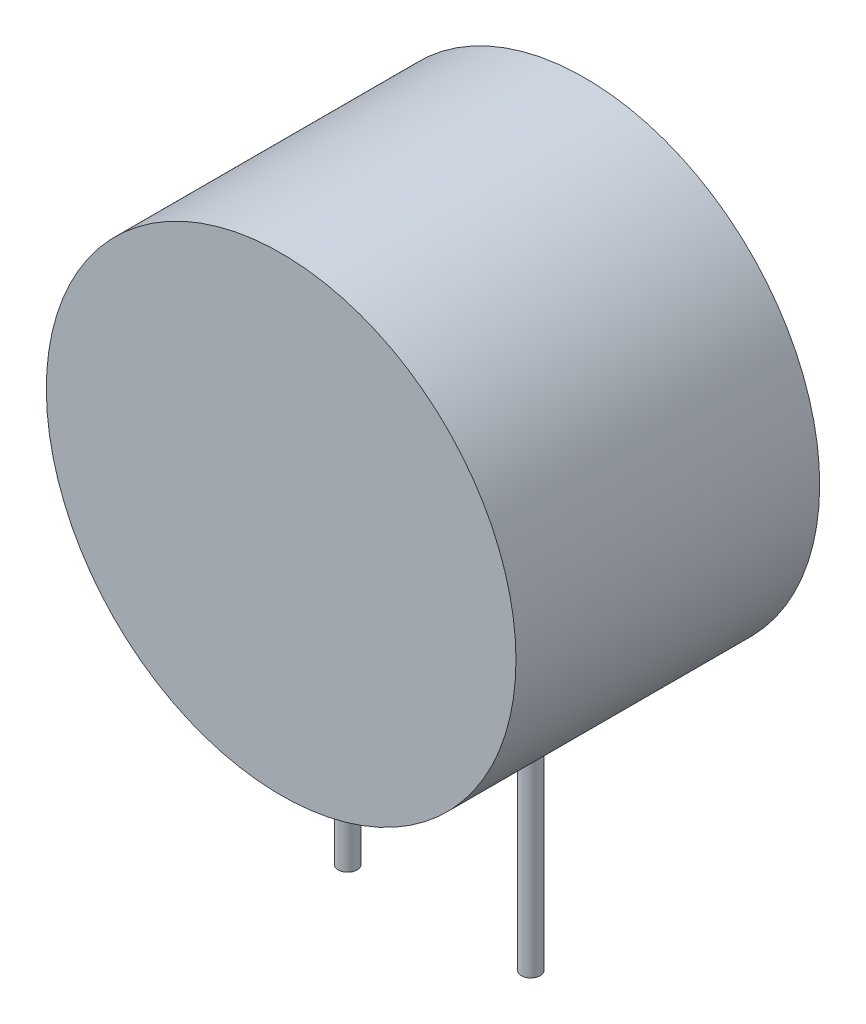
SolidWorks part; units mm, degrees
ref_plane "Front Plane" through (0, 0, 0) normal (0, 0, 1) x (1, 0, 0)
ref_plane "Top Plane" through (0, 0, 0) normal (0, 1, 0) x (1, 0, 0)
ref_plane "Right Plane" through (0, 0, 0) normal (1, 0, 0) x (0, 0, -1)
sketch "Sketch1" plane through (0, 0, 0) normal (0, 0, 1) x (1, 0, 0)
  circle A0 centre (0, 0) radius 75
  dimension "D2" = 150
extrude "Boss-Extrude1" add sketch "Sketch1" along normal blind 97
ref_plane "Plane1" through (0, 0, 77) normal (0, 0, 1) x (1, 0, 0)
ref_plane "Plane2" through (0, 0, 14.5) normal (0, 0, -1) x (-1, 0, 0)
sketch "Sketch2" plane through (0, 0, 14.5) normal (0, 0, -1) x (-1, 0, 0)
  line L0 (35.623, -66) -> (-35.623, -66)
  line L1 (139.8405, -75) -> (-156.115, -75) construction
  circle A0 centre (0, 0) radius 75 construction
  circle A2 centre (0, 0) radius 75
  circle A3 centre (0, 0) radius 75
  dimension "D1" = 9
  dimension "D2" = 0
extrude "Cut-Extrude1" cut sketch "Sketch2" against normal up to surface (62.5 mm away) contours L0 A3
sketch "Sketch3" plane through (0, -66, 0) normal (0, -1, 0) x (1, 0, 0)
  line L0 (0, 0) -> (0, 106.6761) construction
  line L2 (-32.25, 62.7105) -> (-32.25, 7.4276) construction
  line L3 (104.1936, 49.5) -> (-109.669, 49.5) construction
  line L5 (82.5, 77) -> (-82.5, 77) construction
  line L6 (-26.25, 3.6323) -> (-26.25, 73.0939) construction
  line L7 (26.25, 3.6323) -> (26.25, 73.0939) construction
  line L8 (32.25, 62.7105) -> (32.25, 7.4276) construction
  circle A0 centre (-29.25, 46.5) radius 3
  circle A2 centre (29.25, 46.5) radius 3
  dimension "D1" = 6
  dimension "D2" = 27.5
  dimension "D3" = 58.5
  dimension "D4" = 52.5
  dimension "D5" = 64.5
extrude "Boss-Extrude2" add sketch "Sketch3" along normal blind 68
sketch "Sketch4" plane through (0, 0, 0) normal (0, 0, -1) x (-1, 0, 0)
  line L1 (-18.925, -72.573) -> (18.925, -72.573)
  line L2 (-18.925, -72.573) -> (-18.925, -32.573)
  line L3 (-18.925, -32.573) -> (18.925, -32.573)
  line L4 (18.925, -72.573) -> (18.925, -32.573)
  line L5 (-18.925, -72.573) -> (18.925, -32.573) construction
  line L6 (-18.925, -32.573) -> (18.925, -72.573) construction
  circle A0 centre (0, 0) radius 75 construction
  circle A2 centre (0, 0) radius 75
  circle A3 centre (0, 0) radius 75
  point P0 (0, -52.573)
  point P5 (0, 0)
  circle M6 centre (0, 0) radius 75
  dimension "D1" = 37.85
  dimension "D2" = 40
  dimension "D3" = 0
extrude "Boss-Extrude3" add sketch "Sketch4" along normal blind 12.25 contours L1 L4 L3 L2 | L1 M6
